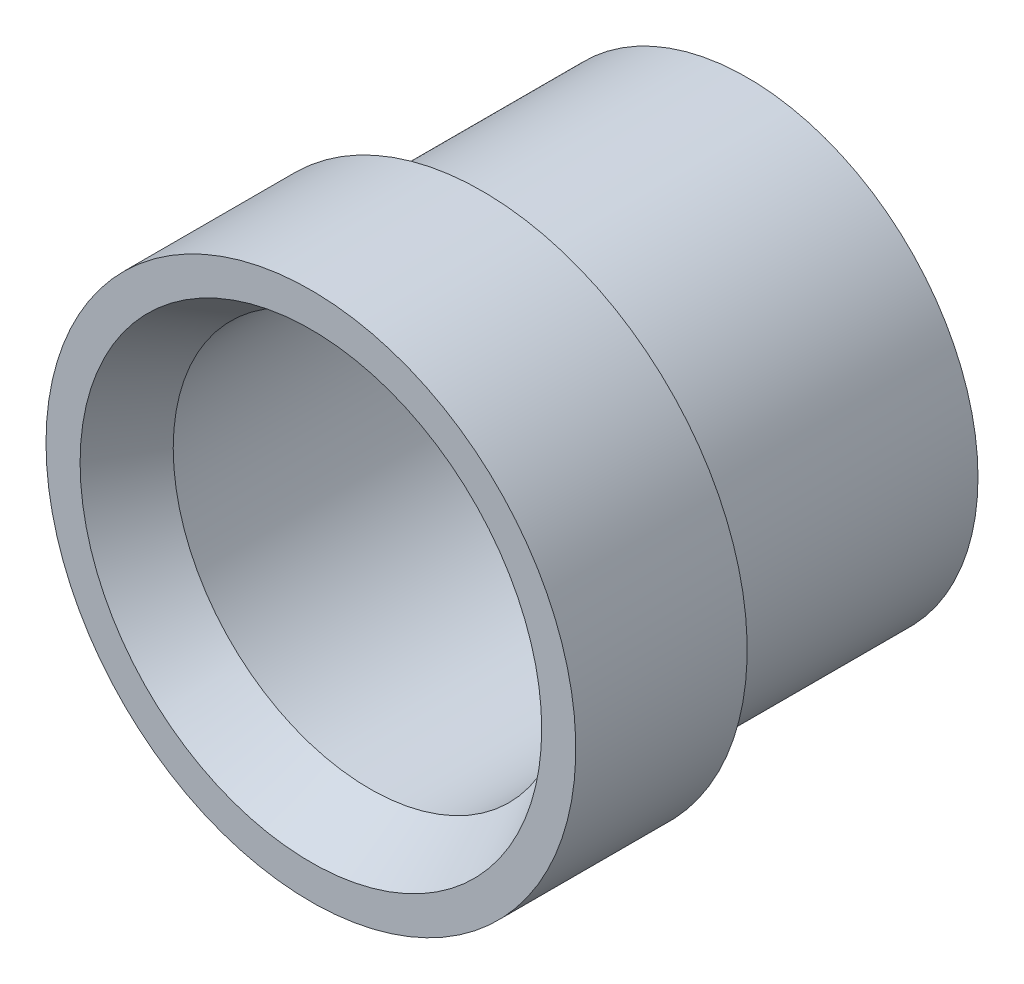
SolidWorks part; units mm, degrees
ref_plane "Front" through (0, 0, 0) normal (0, 0, 1) x (1, 0, 0)
ref_plane "Top" through (0, 0, 0) normal (0, 1, 0) x (1, 0, 0)
ref_plane "Right" through (0, 0, 0) normal (1, 0, 0) x (0, 0, -1)
sketch "Sketch1" plane through (0, 0, 0) normal (1, 0, 0) x (0, 0, -1)
  line L0 (-7.112, 7.5248) -> (-5.1873, 6.4135)
  line L1 (7.112, 6.4135) -> (7.112, 7.5248)
  line L2 (7.112, 7.5248) -> (-1.524, 7.5247)
  line L3 (-1.524, 7.5247) -> (-1.524, 8.636)
  line L4 (-1.524, 8.636) -> (-7.112, 8.636)
  line L5 (-7.112, 8.636) -> (-7.112, 7.5248)
  line L6 (-5.1873, 6.4135) -> (7.112, 6.4135)
  line L7 (7.112, 0) -> (-7.112, 0) construction
  dimension "D1" = 30
  dimension "Length" = 14.224
  dimension "Band" = 5.588
  dimension "Max OD" = 17.272
  dimension "ID" = 12.827
revolve "Revolve1" add sketch "Sketch1" angle 360 about L7
